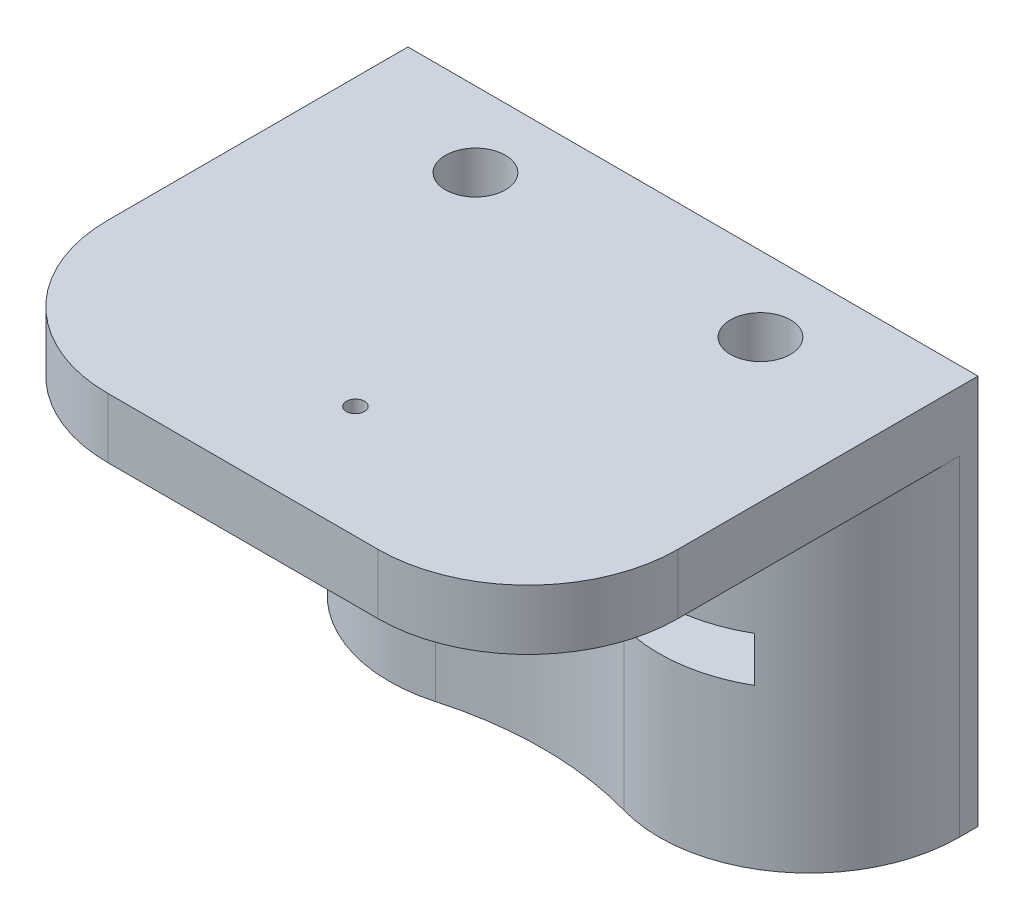
SolidWorks part; units mm, degrees
ref_plane "Alzado" through (0, 0, 0) normal (0, 0, 1) x (1, 0, 0)
ref_plane "Planta" through (0, 0, 0) normal (0, 1, 0) x (1, 0, 0)
ref_plane "Vista lateral" through (0, 0, 0) normal (1, 0, 0) x (0, 0, -1)
sketch "Croquis2" plane through (0, 0, 0) normal (0, 1, 0) x (1, 0, 0)
  line L1 (-43.1071, -17.6252) -> (-5.1071, -17.6252)
  line L2 (-43.1071, -17.6252) -> (-43.1071, -37.6252)
  line L3 (-33.1071, -47.6252) -> (-15.1071, -47.6252)
  line L4 (-5.1071, -17.6252) -> (-5.1071, -37.6252)
  arc A0 (-15.1071, -47.6252) -> (-5.1071, -37.6252) centre (-15.1071, -37.6252) ccw
  arc A1 (-33.1071, -47.6252) -> (-43.1071, -37.6252) centre (-33.1071, -37.6252) cw
  circle A2 centre (-24.1071, -40.1252) radius 0.6
  dimension "D1" = 10
extrude "Saliente-Extruir1" add sketch "Croquis2" along normal blind 4
sketch "Croquis3" plane through (0, 0, 0) normal (0, -1, 0) x (1, 0, 0)
  line L0 (-43.1071, 17.6252) -> (-5.1071, 17.6252)
  line L1 (-43.1071, 17.6252) -> (-43.1071, 37.6252)
  line L3 (-5.1071, 17.6252) -> (-5.1071, 37.6252)
  arc A0 (-43.1071, 37.6252) -> (-5.1071, 37.6252) centre (-24.1071, 50.6752) ccw
extrude "Saliente-Extruir2" add sketch "Croquis3" along normal blind 22
fillet "Redondeo1" radius 10 1 edges at (-43.1071, -11, 37.6252)
fillet "Redondeo2" radius 10 1 edges at (-5.1071, -11, 37.6252)
sketch "Croquis4" plane through (0, 4, 0) normal (0, 1, 0) x (1, 0, 0)
  circle A0 centre (-33.6071, -22.6252) radius 2
  circle A1 centre (-14.6071, -22.6252) radius 2
extrude "Cortar-Extruir1" cut sketch "Croquis4" against normal blind 15.4
sketch "Croquis5" plane through (0, 0, 17.6252) normal (0, 0, -1) x (-1, 0, 0)
  line L4 (29.1071, -8.4) -> (38.1071, -8.4)
  line L5 (38.1071, -8.4) -> (38.1071, -11.4)
  line L6 (38.1071, -11.4) -> (29.1071, -11.4)
  line L7 (29.1071, -8.4) -> (29.1071, -11.4)
  line L8 (19.1071, -8.4) -> (19.1071, -11.4)
  line L9 (10.1071, -11.4) -> (19.1071, -11.4)
  line L10 (10.1071, -8.4) -> (10.1071, -11.4)
  line L11 (19.1071, -8.4) -> (10.1071, -8.4)
extrude "Cortar-Extruir2" cut sketch "Croquis5" against normal blind 12
